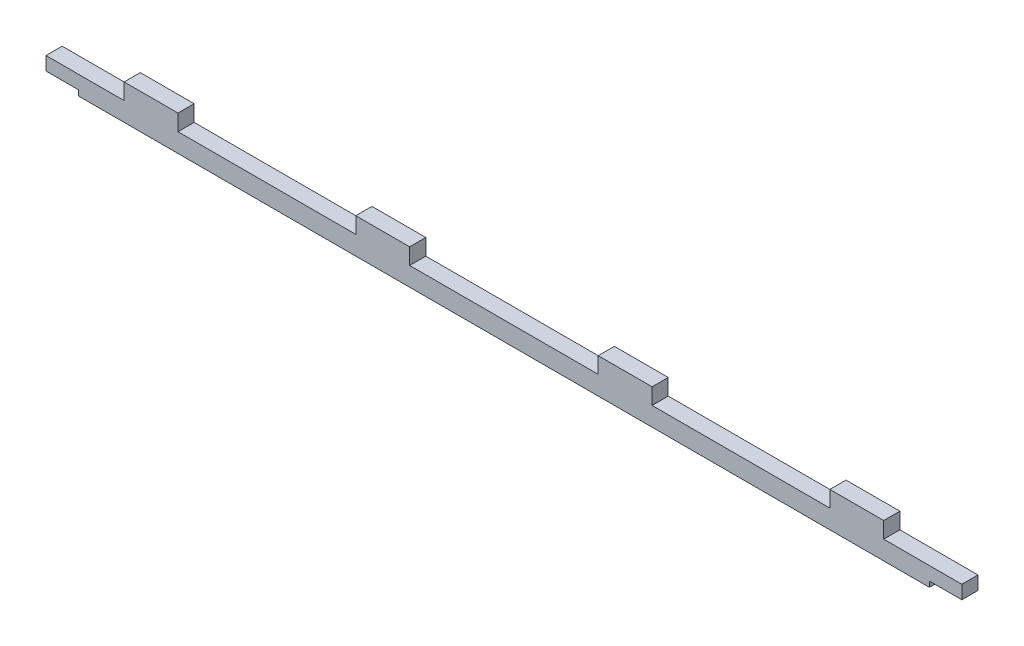
SolidWorks part; units mm, degrees
material "Thornel Mat VMA"
ref_plane "前视基准面" through (0, 0, 0) normal (0, 0, 1) x (1, 0, 0)
ref_plane "上视基准面" through (0, 0, 0) normal (0, 1, 0) x (1, 0, 0)
ref_plane "右视基准面" through (0, 0, 0) normal (1, 0, 0) x (0, 0, -1)
sketch "草图1" plane through (0, 0, 0) normal (0, 0, 1) x (1, 0, 0)
  line L0 (0, 25.2525) -> (0, -19.1002) construction
  line L1 (-29.0692, 0) -> (35.2565, 0) construction
  line L2 (-85, 1) -> (-85, 3.5)
  line L3 (-85, 0) -> (85, 0) construction
  line L4 (-85, 0) -> (-85, 3.5) construction
  line L5 (-85, 3.5) -> (-70.5, 3.5)
  line L6 (85, 0) -> (85, 3.5) construction
  line L7 (-85, 1) -> (-79, 1)
  line L8 (-85, 1) -> (-85, 0) construction
  line L9 (-85, 0) -> (-79, 0) construction
  line L10 (-79, 1) -> (-79, 0)
  line L11 (85, 1) -> (79, 1)
  line L12 (85, 1) -> (85, 0) construction
  line L13 (85, 0) -> (79, 0) construction
  line L14 (79, 1) -> (79, 0)
  line L15 (-79, 0) -> (79, 0)
  line L16 (85, 1) -> (85, 3.5)
  line L17 (-60.5, 3.5) -> (-27.5, 3.5)
  line L18 (-70.5, 6.5) -> (-60.5, 6.5)
  line L19 (-70.5, 6.5) -> (-70.5, 3.5)
  line L21 (-60.5, 6.5) -> (-60.5, 3.5)
  line L22 (-27.5, 6.5) -> (-17.5, 6.5)
  line L23 (-27.5, 6.5) -> (-27.5, 3.5)
  line L25 (-17.5, 6.5) -> (-17.5, 3.5)
  line L27 (17.5, 6.5) -> (17.5, 3.5)
  line L28 (27.5, 6.5) -> (17.5, 6.5)
  line L29 (27.5, 6.5) -> (27.5, 3.5)
  line L31 (60.5, 6.5) -> (60.5, 3.5)
  line L32 (70.5, 6.5) -> (60.5, 6.5)
  line L33 (70.5, 6.5) -> (70.5, 3.5)
  line L34 (-17.5, 3.5) -> (17.5, 3.5)
  line L35 (27.5, 3.5) -> (60.5, 3.5)
  line L36 (70.5, 3.5) -> (85, 3.5)
  point P25 (-65.5, 6.5)
  point P26 (-22.5, 6.5)
  dimension "D1" = 3.5
  dimension "D2" = 170
  dimension "D3" = 2.5
  dimension "D4" = 6
  dimension "D5" = 43
  dimension "D6" = 10
  dimension "D7" = 3
  dimension "D8" = 45
extrude "凸台-拉伸1" add sketch "草图1" along normal blind 3
